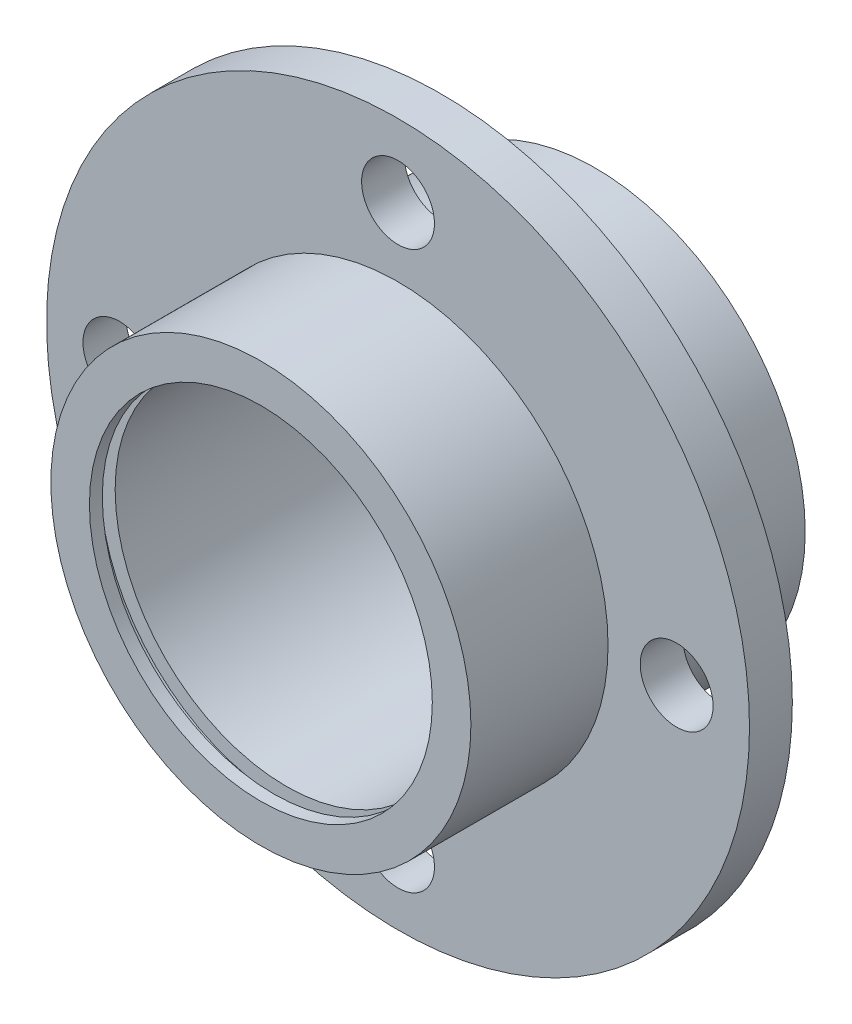
SolidWorks part; units mm, degrees
ref_plane "前视基准面" through (0, 0, 0) normal (0, 0, 1) x (1, 0, 0)
ref_plane "上视基准面" through (0, 0, 0) normal (0, 1, 0) x (1, 0, 0)
ref_plane "右视基准面" through (0, 0, 0) normal (1, 0, 0) x (0, 0, -1)
sketch "草图1" plane through (0, 0, 0) normal (0, 0, 1) x (1, 0, 0)
  circle A0 centre (0, 0) radius 24.5
  dimension "D1" = 49
extrude "凸台-拉伸1" add sketch "草图1" along normal blind 39
sketch "草图2" plane through (0, 0, 39) normal (0, 0, 1) x (1, 0, 0)
  circle A0 centre (0, 0) radius 20
  dimension "D1" = 40
extrude "切除-拉伸1" cut sketch "草图2" against normal blind 36
sketch "草图3" plane through (0, 0, 3) normal (0, 0, 1) x (1, 0, 0)
  circle A0 centre (0, 0) radius 15
  dimension "D1" = 30
extrude "切除-拉伸2" cut sketch "草图3" against normal through all
sketch "草图4" plane through (0, 0, 3) normal (0, 0, 1) x (1, 0, 0)
  circle A0 centre (0, 0) radius 21.75
  dimension "D1" = 43.5
extrude "切除-拉伸3" cut sketch "草图4" along normal blind 1.5 from offset 33
sketch "草图5" plane through (0, 0, 39) normal (0, 0, 1) x (1, 0, 0)
  circle A0 centre (0, 0) radius 41
  circle A2 centre (0, 0) radius 24.5
  circle A3 centre (0, 0) radius 24.5
  point P3 (-0.3881, 0)
  dimension "D1" = 82
  dimension "D2" = 0
extrude "凸台-拉伸2" add sketch "草图5" against normal blind 5 from offset 16 offset against normal yes
sketch "草图6" plane through (0, 0, 23) normal (0, 0, 1) x (1, 0, 0)
  circle A0 centre (0, 0) radius 32.5 construction
  circle A1 centre (32.5, 0) radius 4.25
  dimension "D1" = 65
  dimension "D2" = 8.5
extrude "切除-拉伸4" cut sketch "草图6" against normal through all
pattern_circular "阵列(圆周)1" count 4 over 360 about axis through (0, 0, 0) along (0, 0, 1) of "切除-拉伸4"
